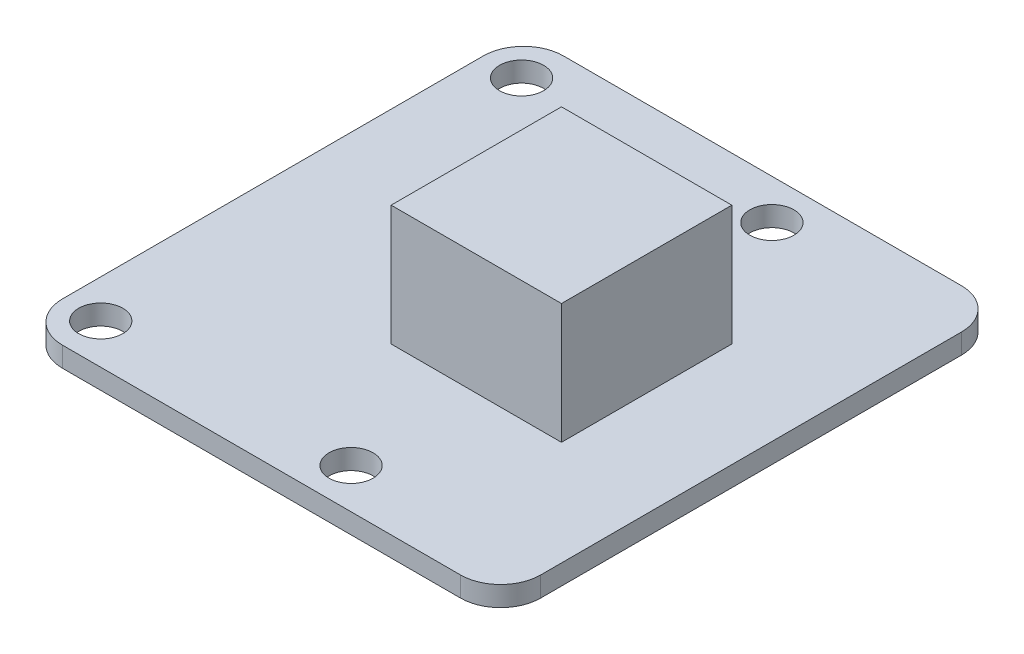
SolidWorks part; units mm, degrees
ref_plane "Front Plane" through (0, 0, 0) normal (0, 0, 1) x (1, 0, 0)
ref_plane "Top Plane" through (0, 0, 0) normal (0, 1, 0) x (1, 0, 0)
ref_plane "Right Plane" through (0, 0, 0) normal (1, 0, 0) x (0, 0, -1)
sketch "Sketch1" plane through (0, 0, 0) normal (0, 1, 0) x (1, 0, 0)
  line L0 (-11.931, 0) -> (11.931, 0) construction
  line L1 (-11.931, -12.5) -> (11.931, -12.5)
  line L2 (-11.931, -12.5) -> (-11.931, 12.5)
  line L3 (-11.931, 12.5) -> (11.931, 12.5)
  line L4 (11.931, -12.5) -> (11.931, 12.5)
  line L5 (-11.931, -12.5) -> (11.931, 12.5) construction
  line L6 (-11.931, 12.5) -> (11.931, -12.5) construction
  circle A0 centre (-10.022, 10.5) radius 1.1
  circle A1 centre (2.469, 10.5) radius 1.1
  circle A2 centre (2.469, -10.5) radius 1.1
  circle A3 centre (-10.022, -10.5) radius 1.1
  point P0 (0, 0)
  point P16 (0, 0)
  dimension "D3" = 2.2
  dimension "D4" = 2.2
  dimension "D1" = 23.862
  dimension "D2" = 25
  dimension "D5" = 2
  dimension "D6" = 2
  dimension "D7" = 9.462
extrude "Boss-Extrude1" add sketch "Sketch1" along normal blind 1
fillet "Fillet1" radius 2 4 edges at (-11.931, 0.5, -12.5) (-11.931, 0.5, 12.5) (11.931, 0.5, -12.5) (11.931, 0.5, 12.5)
sketch "Sketch2" plane through (0, 1, 0) normal (0, 1, 0) x (1, 0, 0)
  line L0 (2.469, 10.5) -> (2.469, -10.5) construction
  line L1 (-11.931, 0) -> (11.931, 0) construction
  line L2 (-11.931, 10.5) -> (-11.931, -10.5) construction
  line L3 (11.931, -10.5) -> (11.931, 10.5) construction
  line L5 (-1.781, -4.25) -> (6.719, -4.25)
  line L6 (-1.781, -4.25) -> (-1.781, 4.25)
  line L7 (-1.781, 4.25) -> (6.719, 4.25)
  line L8 (6.719, -4.25) -> (6.719, 4.25)
  line L9 (-1.781, -4.25) -> (6.719, 4.25) construction
  line L10 (-1.781, 4.25) -> (6.719, -4.25) construction
  point P10 (2.469, 0)
  dimension "D1" = 8.5
  dimension "D2" = 8.5
extrude "Boss-Extrude2" add sketch "Sketch2" along normal blind 6
